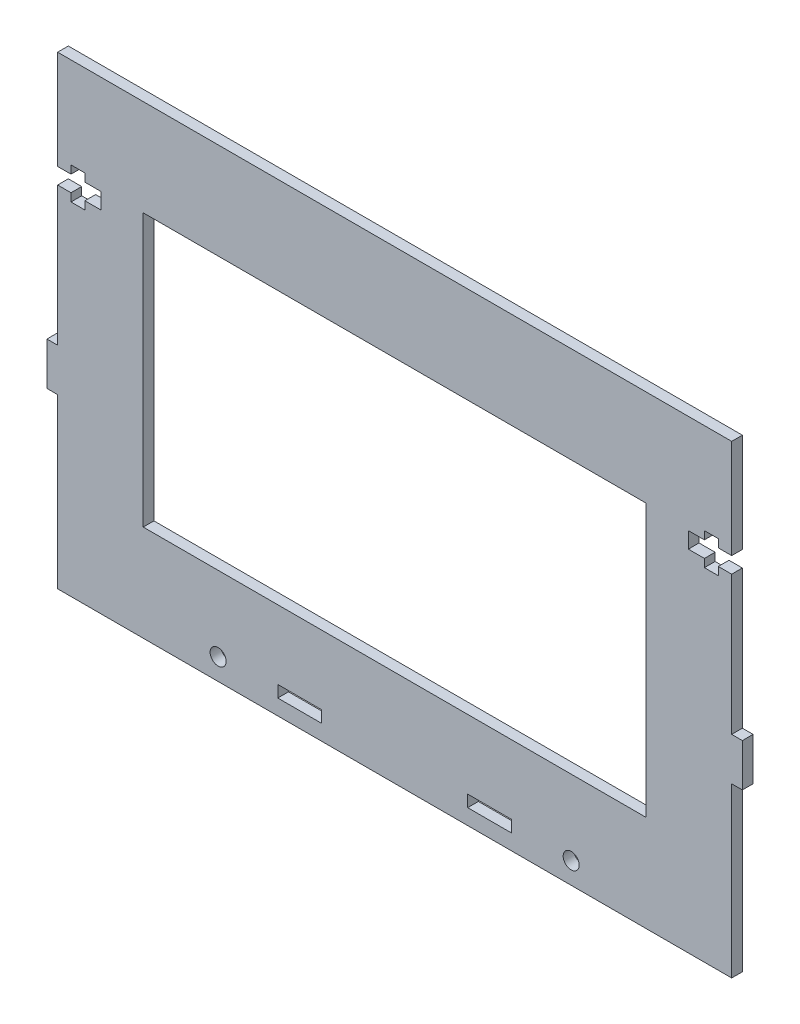
SolidWorks part; units mm, degrees
ref_plane "前视基准面" through (0, 0, 0) normal (0, 0, 1) x (1, 0, 0)
ref_plane "上视基准面" through (0, 0, 0) normal (0, 1, 0) x (1, 0, 0)
ref_plane "右视基准面" through (0, 0, 0) normal (1, 0, 0) x (0, 0, -1)
sketch "草图1" plane through (0, 0, 0) normal (0, 0, 1) x (1, 0, 0)
  line L0 (-62.7662, -53.1995) -> (-62.7662, -54.6995)
  line L1 (-24.1162, -115.6745) -> (-15.9162, -115.6745)
  line L2 (-15.9162, -113.4745) -> (-15.9162, -115.6745)
  line L3 (-24.1162, -113.4745) -> (-15.9162, -113.4745)
  line L4 (-24.1162, -113.4745) -> (-24.1162, -115.6745)
  line L5 (19.5838, -113.4745) -> (19.5838, -115.6745)
  line L6 (19.5838, -113.4745) -> (11.3838, -113.4745)
  line L7 (11.3838, -113.4745) -> (11.3838, -115.6745)
  line L10 (19.5838, -115.6745) -> (11.3838, -115.6745)
  line L12 (-57.1662, -50.1995) -> (-57.1662, -53.1995)
  line L13 (-49.2662, -100.5745) -> (-49.2662, -49.6995)
  line L15 (-62.7662, -50.1995) -> (-62.7662, -48.6995)
  line L16 (-65.2662, -79.137) -> (-67.2662, -79.137)
  line L17 (-67.2662, -79.137) -> (-67.2662, -87.137)
  line L18 (-67.2662, -87.137) -> (-65.2662, -87.137)
  line L19 (-65.2662, -87.137) -> (-65.2662, -118.5745)
  line L20 (-65.2662, -50.1995) -> (-62.7662, -50.1995)
  line L21 (-62.7662, -54.6995) -> (-60.1662, -54.6995)
  line L22 (-60.1662, -54.6995) -> (-60.1662, -53.1995)
  line L23 (-60.1662, -53.1995) -> (-57.1662, -53.1995)
  line L25 (-60.1662, -50.1995) -> (-57.1662, -50.1995)
  line L26 (-60.1662, -48.6995) -> (-60.1662, -50.1995)
  line L27 (-62.7662, -48.6995) -> (-60.1662, -48.6995)
  line L28 (-62.7662, -53.1995) -> (-65.2662, -53.1995)
  line L30 (-65.2662, -51.6995) -> (-63.6388, -51.6995) construction
  line L31 (-65.2662, -53.1995) -> (-65.2662, -79.137)
  line L38 (-35.2662, -114.5745) -> (-24.1162, -114.5745) construction
  line L60 (-65.2662, -31.6995) -> (60.7338, -31.6995)
  line L63 (60.7338, -87.137) -> (60.7338, -118.5745)
  line L64 (60.7338, -51.6995) -> (59.1065, -51.6995) construction
  line L66 (19.5838, -114.5745) -> (30.7338, -114.5745) construction
  line L87 (-65.2662, -50.1995) -> (-65.2662, -31.6995)
  line L90 (60.7338, -53.1995) -> (60.7338, -79.137)
  line L91 (58.2338, -53.1995) -> (60.7338, -53.1995)
  line L92 (58.2338, -48.6995) -> (55.6338, -48.6995)
  line L93 (55.6338, -48.6995) -> (55.6338, -50.1995)
  line L94 (55.6338, -50.1995) -> (52.6338, -50.1995)
  line L96 (55.6338, -53.1995) -> (52.6338, -53.1995)
  line L97 (55.6338, -54.6995) -> (55.6338, -53.1995)
  line L98 (58.2338, -54.6995) -> (55.6338, -54.6995)
  line L99 (60.7338, -50.1995) -> (58.2338, -50.1995)
  line L101 (62.7338, -87.137) -> (60.7338, -87.137)
  line L102 (62.7338, -79.137) -> (62.7338, -87.137)
  line L103 (60.7338, -79.137) -> (62.7338, -79.137)
  line L104 (58.2338, -50.1995) -> (58.2338, -48.6995)
  line L105 (52.6338, -50.1995) -> (52.6338, -53.1995)
  line L106 (58.2338, -53.1995) -> (58.2338, -54.6995)
  line L110 (60.7338, -31.6995) -> (60.7338, -50.1995)
  line L117 (62.7338, -118.5745) -> (-67.2662, -118.5745) construction
  line L118 (62.7338, -118.5745) -> (62.7338, -31.6995) construction
  line L119 (62.7338, -31.6995) -> (-67.2662, -31.6995) construction
  line L120 (-67.2662, -118.5745) -> (-67.2662, -31.6995) construction
  line L121 (44.7338, -49.6995) -> (-49.2662, -49.6995)
  line L122 (44.7338, -100.5745) -> (44.7338, -49.6995)
  line L123 (44.7338, -100.5745) -> (-49.2662, -100.5745)
  line L124 (60.7338, -118.5745) -> (-65.2662, -118.5745)
  circle A0 centre (-35.2662, -114.5745) radius 1.5
  circle A1 centre (30.7338, -114.5745) radius 1.5
  dimension "D1" = 18
extrude "凸台-拉伸1" add sketch "草图1" along normal blind 2 contours L20 L15 L27 L26 L25 L12 L23 L22 L21 L0 L28 L31 L16 L17 L18 L19
